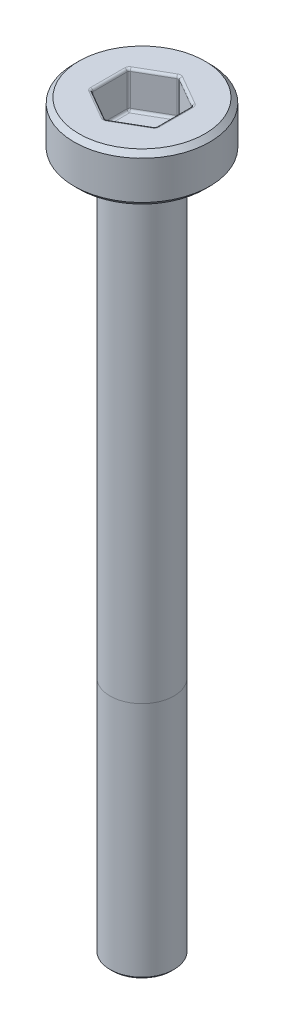
SolidWorks part; units mm, degrees
ref_plane "Front Plane" through (0, 0, 0) normal (0, 0, 1) x (1, 0, 0)
ref_plane "Top Plane" through (0, 0, 0) normal (0, 1, 0) x (1, 0, 0)
ref_plane "Right Plane" through (0, 0, 0) normal (1, 0, 0) x (0, 0, -1)
sketch "Sketch1" plane through (0, 0, 0) normal (0, 1, 0) x (1, 0, 0)
  circle A0 centre (0, 0) radius 1
  dimension "D1" = 2
extrude "Boss-Extrude1" add sketch "Sketch1" along normal blind 21.75
sketch "Sketch2" plane through (0, 21.75, 0) normal (0, 1, 0) x (1, 0, 0)
  circle A0 centre (0, 0) radius 2.125
  dimension "D1" = 4.25
extrude "Boss-Extrude2" add sketch "Sketch2" along normal blind 1.5
fillet "Fillet1" radius 0.15 1 edges at (0, 21.75, 1)
chamfer "Chamfer1" distance 0.15 angle 45 2 edges at (0, 23.25, 2.125) (0, 21.75, 2.125)
sketch "Sketch3" plane through (0, 23.25, 0) normal (0, 1, 0) x (1, 0, 0)
  line L1 (0, 1.1547) -> (-1, 0.5774)
  line L2 (-1, 0.5774) -> (-1, -0.5774)
  line L3 (-1, -0.5774) -> (0, -1.1547)
  line L4 (0, -1.1547) -> (1, -0.5774)
  line L5 (1, -0.5774) -> (1, 0.5774)
  line L6 (1, 0.5774) -> (0, 1.1547)
  circle A0 centre (0, 0) radius 1 construction
  dimension "D1" = 2
extrude "Cut-Extrude1" cut sketch "Sketch3" against normal blind 1.15
chamfer "Chamfer2" distance 0.075 angle 45 1 edges at (0, 0, 1)
fillet "Fillet2" radius 0.075 18 edges at (0.5, 23.25, -0.866) (-0.5, 23.25, -0.866) (-1, 23.25, 0) (-0.5, 23.25, 0.866) (0.5, 23.25, 0.866) (1, 23.25, 0) (-0.5, 22.1, -0.866) (-1, 22.1, 0) (-0.5, 22.1, 0.866) (0.5, 22.1, 0.866) (1, 22.1, 0) (0, 22.675, -1.1547) (-1, 22.675, -0.5774) (-1, 22.675, 0.5774) (0, 22.675, 1.1547) (1, 22.675, 0.5774) (1, 22.675, -0.5774) (0.5, 22.1, -0.866)
sketch "Sketch4" plane through (0, 0, 0) normal (0, 0, 1) x (1, 0, 0)
  line L0 (-5.6741, 7.5) -> (6.8738, 7.5)
  dimension "D1" = 7.5
split line "Split Line1"
